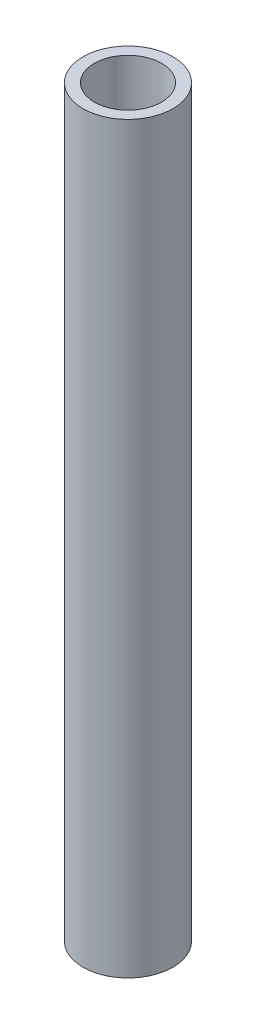
SolidWorks part; units mm, degrees
ref_plane "Front Plane" through (0, 0, 0) normal (0, 0, 1) x (1, 0, 0)
ref_plane "Top Plane" through (0, 0, 0) normal (0, 1, 0) x (1, 0, 0)
ref_plane "Right Plane" through (0, 0, 0) normal (1, 0, 0) x (0, 0, -1)
sketch "Sketch1" plane through (0, 0, 0) normal (0, 1, 0) x (1, 0, 0)
  circle A0 centre (0, 0) radius 9.5
  circle A1 centre (0, 0) radius 12.7
  dimension "D1" = 19
  dimension "D2" = 25.4
extrude "Boss-Extrude1" add sketch "Sketch1" along normal blind 210
